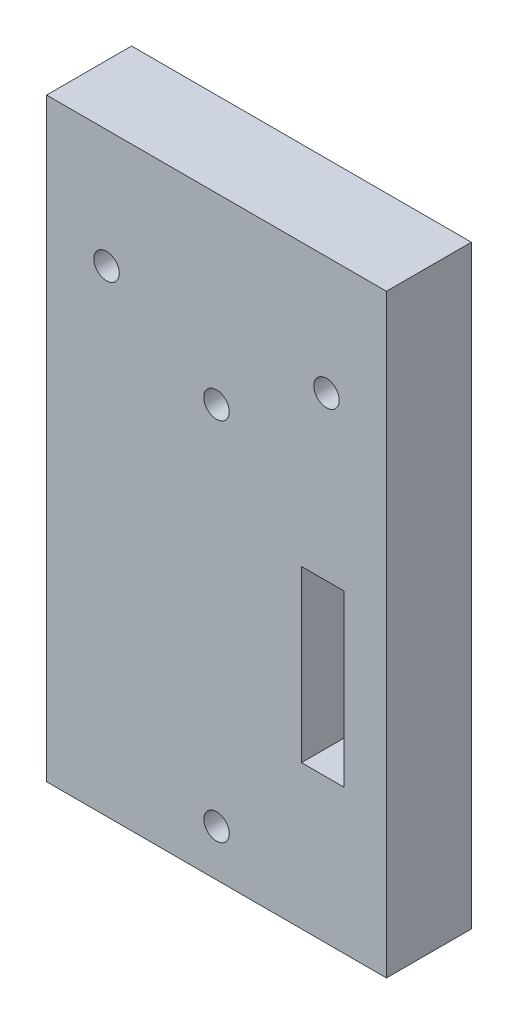
SolidWorks part; units mm, degrees
ref_plane "前基準面" through (0, 0, 0) normal (0, 0, 1) x (1, 0, 0)
ref_plane "上基準面" through (0, 0, 0) normal (0, 1, 0) x (1, 0, 0)
ref_plane "右基準面" through (0, 0, 0) normal (1, 0, 0) x (0, 0, -1)
sketch "草圖1" plane through (0, 0, 0) normal (0, 0, 1) x (1, 0, 0)
  line L0 (0, 21.5) -> (0, -21.5) construction
  line L1 (-20, 43.0466) -> (20, 43.0466)
  line L2 (-20, 43.0466) -> (-20, -26.9534)
  line L3 (-20, -26.9534) -> (20, -26.9534)
  line L4 (20, 43.0466) -> (20, -26.9534)
  line L5 (0, 29.1431) -> (0, 43.0466) construction
  line L7 (10, 10) -> (15, 10)
  line L8 (10, 10) -> (10, -10)
  line L9 (10, -10) -> (15, -10)
  line L10 (15, 10) -> (15, -10)
  line L11 (0, 0) -> (10, 0) construction
  line L12 (-12.9453, 29.1431) -> (12.9453, 29.1431) construction
  circle A0 centre (12.9453, 29.1431) radius 1.5
  circle A1 centre (-12.9453, 29.1431) radius 1.5
  circle A2 centre (0, -21.5) radius 1.5
  circle A3 centre (0, 21.5) radius 1.5
  point P0 (0, 0)
  dimension "D3" = 3
  dimension "D4" = 43
  dimension "D1" = 5
  dimension "D2" = 20
  dimension "D5" = 10
  dimension "D6" = 40
  dimension "D7" = 70
  dimension "D8" = 20
extrude "伸長1" add sketch "草圖1" along normal blind 10
